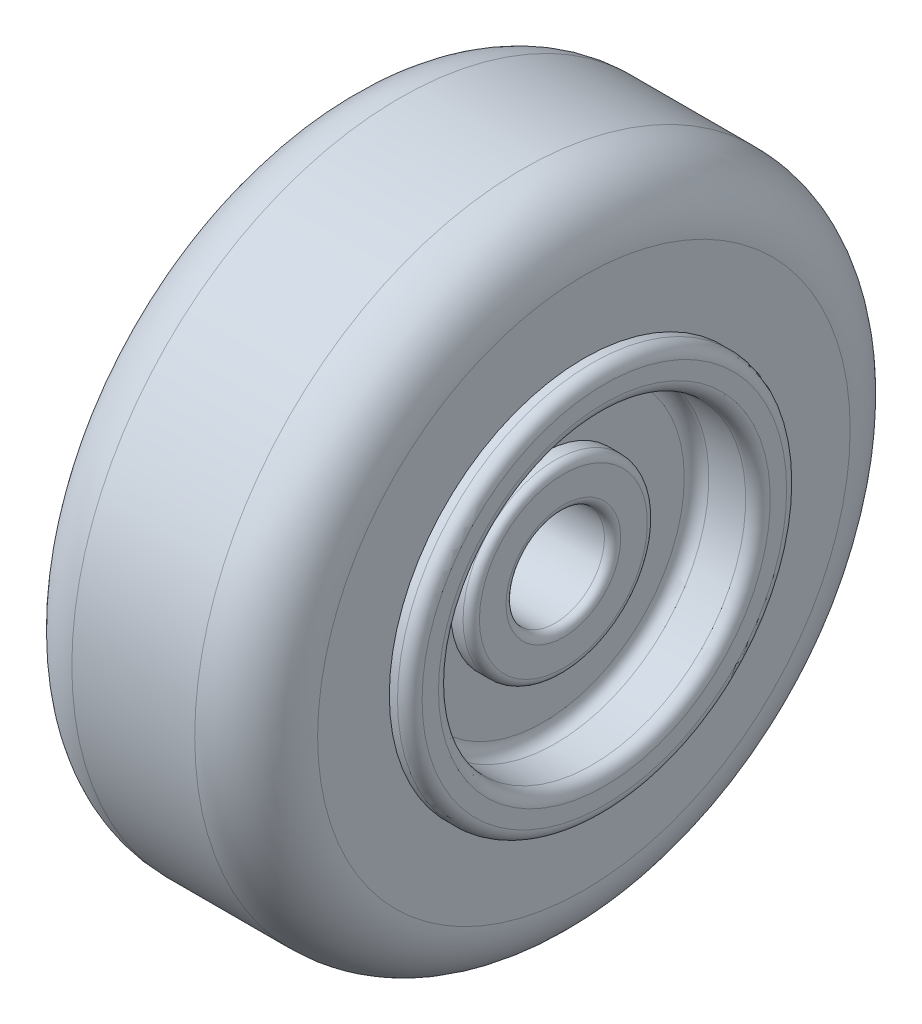
SolidWorks part; units mm, degrees
ref_plane "Plano frontal" through (0, 0, 0) normal (0, 0, 1) x (1, 0, 0)
ref_plane "Plano superior" through (0, 0, 0) normal (0, 1, 0) x (1, 0, 0)
ref_plane "Plano direito" through (0, 0, 0) normal (1, 0, 0) x (0, 0, -1)
sketch "Esboço1" plane through (0, 0, 0) normal (1, 0, 0) x (0, 0, -1)
  circle A6 centre (0, 0) radius 8
  circle A7 centre (0, 0) radius 4.75
  circle A8 centre (0, 0) radius 1.75
  dimension "D1" = 3.5
  dimension "D2" = 16
  dimension "D3" = 9.5
sketch "Esboço2" plane through (0, 0, 0) normal (0, 0, 1) x (1, 0, 0)
  line L0 (0, 0) -> (12.6911, 0) construction
  line L1 (0, 0) -> (0, 12.8674) construction
  line L2 (-2.3, 1.2) -> (2.3, 1.2)
  line L8 (-1.5, 8) -> (1.5, 8)
  line L9 (-2.3, 2.25) -> (-2, 2.25)
  line L11 (3, 6.5) -> (3, 4.75)
  line L12 (3, 4.75) -> (3.2, 4.75)
  line L13 (3.5, 4.45) -> (3.5, 4.05)
  line L14 (3.2, 3.75) -> (2.3, 3.75)
  line L15 (2, 3.45) -> (2, 2.25)
  line L17 (2.5, 1.4) -> (2.5, 2.05)
  line L18 (2.3, 2.25) -> (2, 2.25)
  line L19 (-2.5, 1.4) -> (-2.5, 2.05)
  line L21 (-2, 3.45) -> (-2, 2.25)
  line L22 (-3.2, 3.75) -> (-2.3, 3.75)
  line L23 (-3.5, 4.45) -> (-3.5, 4.05)
  line L24 (-3, 4.75) -> (-3.2, 4.75)
  line L25 (-3, 6.5) -> (-3, 4.75)
  arc A0 (2.3, 3.75) -> (2, 3.45) centre (2.3, 3.45) ccw
  arc A1 (3.5, 4.05) -> (3.2, 3.75) centre (3.2, 4.05) cw
  arc A2 (3.2, 4.75) -> (3.5, 4.45) centre (3.2, 4.45) cw
  arc A3 (2.5, 2.05) -> (2.3, 2.25) centre (2.3, 2.05) ccw
  arc A4 (1.5, 8) -> (3, 6.5) centre (1.5, 6.5) cw
  arc A5 (-1.5, 8) -> (-3, 6.5) centre (-1.5, 6.5) ccw
  arc A6 (-2.5, 2.05) -> (-2.3, 2.25) centre (-2.3, 2.05) cw
  arc A7 (-3.2, 4.75) -> (-3.5, 4.45) centre (-3.2, 4.45) ccw
  arc A8 (-3.5, 4.05) -> (-3.2, 3.75) centre (-3.2, 4.05) ccw
  arc A9 (-2.3, 3.75) -> (-2, 3.45) centre (-2.3, 3.45) cw
  arc A10 (2.5, 1.4) -> (2.3, 1.2) centre (2.3, 1.4) cw
  arc A11 (-2.5, 1.4) -> (-2.3, 1.2) centre (-2.3, 1.4) ccw
  point P3 (0, 1.75)
  point P5 (0, 4.75)
  point P6 (0, 8)
  point P9 (0, 8)
  point P13 (-3, 8)
  point P23 (3.5, 3.75)
  point P26 (3.5, 4.75)
  point P32 (2.5, 2.25)
  point P34 (3, 8)
  point P54 (0, 1.75)
  point P55 (-2.5, 2.25)
  point P56 (-3.5, 4.75)
  point P57 (-3.5, 3.75)
  dimension "D5" = 0.3
  dimension "D8" = 0.2
  dimension "D9" = 1.5
  dimension "D6" = 0.2
  dimension "D1" = 3
  dimension "D2" = 0.5
  dimension "D3" = 1
  dimension "D4" = 2
  dimension "D10" = 1.2
revolve "Revolução1" add sketch "Esboço2" angle 360 about L0
